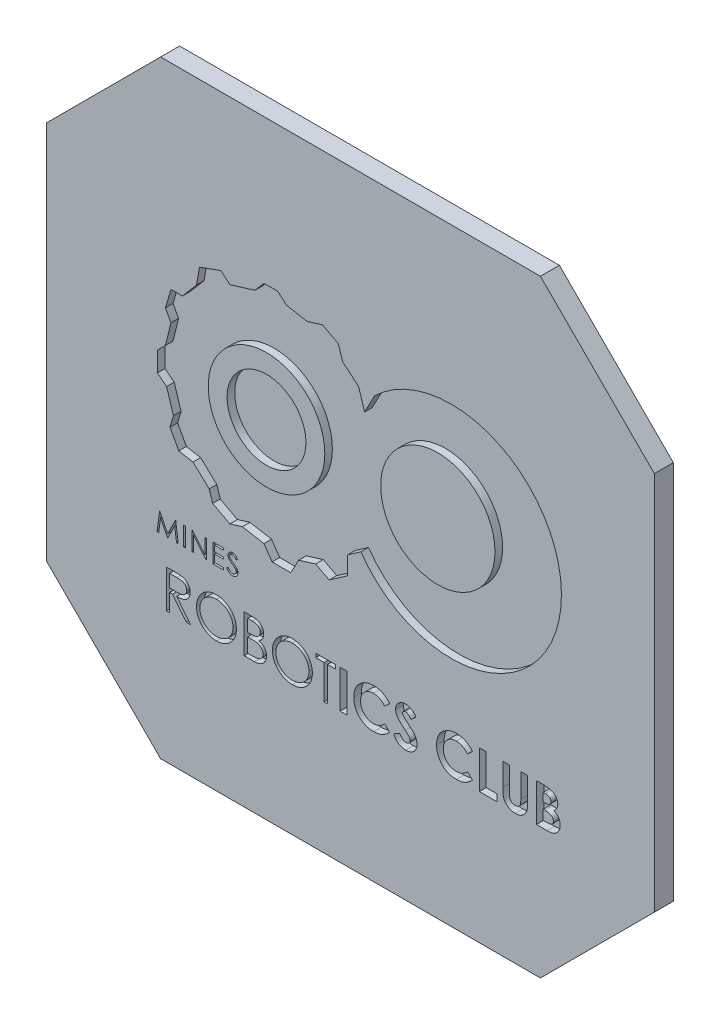
SolidWorks part; units mm, degrees
ref_plane "Front Plane" through (0, 0, 0) normal (0, 0, 1) x (1, 0, 0)
ref_plane "Top Plane" through (0, 0, 0) normal (0, 1, 0) x (1, 0, 0)
ref_plane "Right Plane" through (0, 0, 0) normal (1, 0, 0) x (0, 0, -1)
sketch "Sketch1" plane through (0, 0, 0) normal (0, 0, 1) x (1, 0, 0)
  line L8 (-80, -50) -> (-50, -80)
  line L9 (-50, -80) -> (50, -80)
  line L10 (50, -80) -> (80, -50)
  line L11 (80, -50) -> (80, 50)
  line L12 (80, 50) -> (50, 80)
  line L13 (50, 80) -> (-50, 80)
  line L14 (-50, 80) -> (-80, 50)
  line L15 (-80, 50) -> (-80, -50)
  line L16 (-80, -50) -> (-50, -80)
  line L17 (-50, -80) -> (50, -80)
  line L18 (50, -80) -> (80, -50)
  line L19 (80, -50) -> (80, 50)
  line L20 (80, 50) -> (50, 80)
  line L21 (50, 80) -> (-50, 80)
  line L22 (-50, 80) -> (-80, 50)
  line L23 (-80, 50) -> (-80, -50)
  dimension "D1" = 0
extrude "Boss-Extrude1" add sketch "Sketch1" along normal blind 5
sketch "Sketch4" plane through (0, 0, 5) normal (0, 0, -1) x (-1, 0, 0)
  line L0 (-134.1705, 42.8552) -> (267.8295, 42.8552) construction
  line L1 (36.3045, -14.9409) -> (31.7575, -17.3481)
  line L2 (31.7575, -17.3481) -> (28.4589, -16.3332)
  line L3 (28.4589, -16.3332) -> (22.7972, -17.3481)
  line L4 (22.7972, -17.3481) -> (20.6377, -20.451)
  line L5 (20.6377, -20.451) -> (15.7092, -20.451)
  line L6 (15.7092, -20.451) -> (13.6519, -16.565)
  line L7 (13.6519, -16.565) -> (9.1636, -15.184)
  line L8 (9.1636, -15.184) -> (5.6206, -17.0596)
  line L9 (5.6206, -17.0596) -> (0.7412, -13.6637)
  line L10 (0.7412, -13.6637) -> (0.7412, -8.8811)
  line L11 (0.7412, -8.8811) -> (-2.7365, -6.4607)
  line L12 (-6.3573, 30.9306) -> (-3.693, 25.8981)
  line L13 (-3.693, 25.8981) -> (-2.1606, 30.8786)
  line L14 (-2.1606, 30.8786) -> (2.1089, 34.5168)
  line L15 (2.1089, 34.5168) -> (3.1809, 38.0008)
  line L16 (3.1809, 38.0008) -> (7.3921, 40.2303)
  line L17 (7.3921, 40.2303) -> (11.4077, 38.9947)
  line L18 (11.4077, 38.9947) -> (16.7785, 39.9575)
  line L19 (16.7785, 39.9575) -> (19.1625, 41.989)
  line L20 (19.1625, 41.989) -> (22.7972, 41.989)
  line L21 (22.7972, 41.989) -> (25.1464, 39.2321)
  line L22 (25.1464, 39.2321) -> (31.7575, 37.1979)
  line L23 (31.7575, 37.1979) -> (34.1447, 39.2321)
  line L24 (34.1447, 39.2321) -> (39.7609, 37.1979)
  line L25 (39.7609, 37.1979) -> (40.5677, 32.6977)
  line L26 (40.5677, 32.6977) -> (44.2397, 28.3884)
  line L27 (44.2397, 28.3884) -> (47.2709, 28.3884)
  line L28 (47.2709, 28.3884) -> (48.7278, 23.4414)
  line L29 (48.7278, 23.4414) -> (47.2709, 20.7681)
  line L30 (47.2709, 20.7681) -> (48.7278, 14.8337)
  line L31 (48.7278, 14.8337) -> (50.8381, 12.7367)
  line L32 (50.8381, 12.7367) -> (50.8381, 7.5375)
  line L33 (50.8381, 7.5375) -> (48.4252, 5.6417)
  line L34 (48.4252, 5.6417) -> (46.6155, -0.1033)
  line L35 (46.6155, -0.1033) -> (47.5204, -3.1757)
  line L36 (47.5204, -3.1757) -> (45.2073, -7.4199)
  line L37 (45.2073, -7.4199) -> (41.4738, -8.0888)
  line L38 (41.4738, -8.0888) -> (37.1938, -12.0816)
  line L39 (37.1938, -12.0816) -> (36.3045, -14.9409)
  arc A0 (-2.7365, -6.4607) -> (-6.3573, 30.9306) centre (-26.5392, 10.1053) cw
  text T0 "<b>ROBOTICS</b> CLUB" font "Century Gothic" height 10
  text T1 "MINES" font "Century Gothic" height 5
  point P44 (0, 0)
  point P46 (0, 0)
  dimension "D1" = 29
extrude "Cut-Extrude1" cut sketch "Sketch4" along normal blind 2
sketch "Sketch5" plane through (0, 0, 3) normal (0, 0, 1) x (1, 0, 0)
  line L0 (10.9629, 198.3636) -> (412.9629, 198.3636) construction
  circle A0 centre (-22.1124, 11.2094) radius 15.3476
  circle A1 centre (-22.1124, 11.2094) radius 10.3786
  circle A2 centre (22.9917, 11.2094) radius 15.0526
extrude "Boss-Extrude2" add sketch "Sketch5" along normal blind 2
